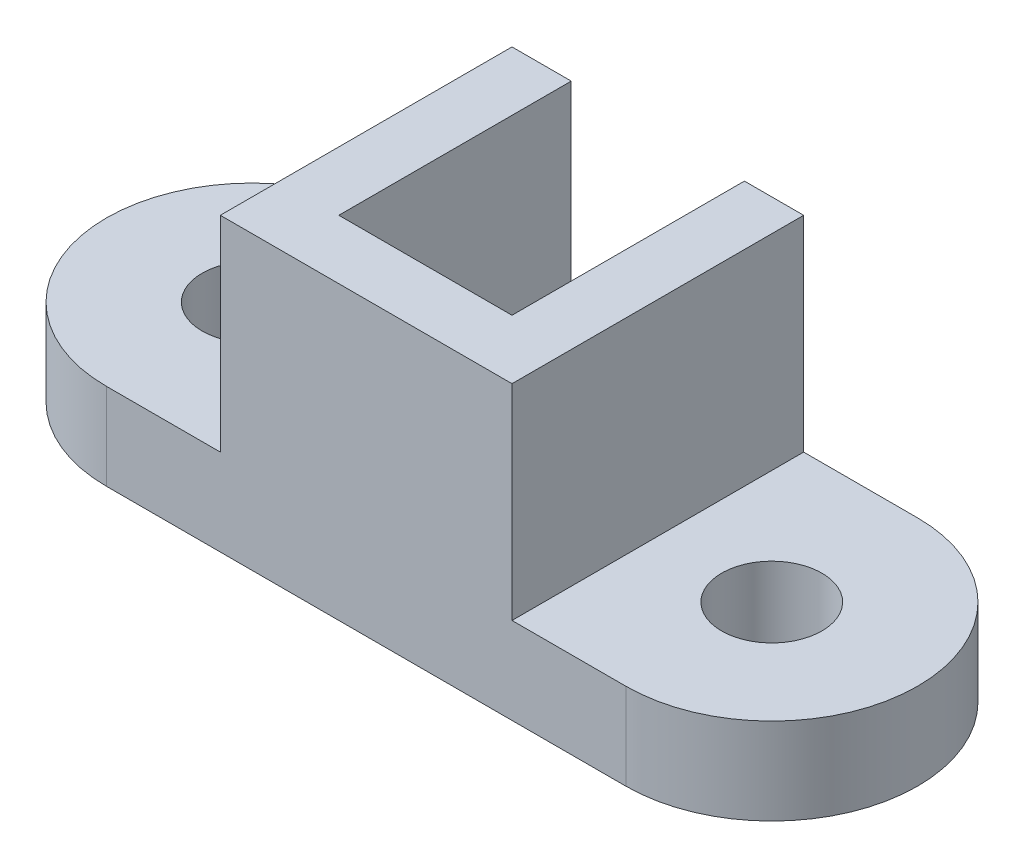
SolidWorks part; units mm, degrees
ref_plane "Front Plane" through (0, 0, 0) normal (0, 0, 1) x (1, 0, 0)
ref_plane "Top Plane" through (0, 0, 0) normal (0, 1, 0) x (1, 0, 0)
ref_plane "Right Plane" through (0, 0, 0) normal (1, 0, 0) x (0, 0, -1)
sketch "Sketch1" plane through (0, 0, 0) normal (0, 1, 0) x (1, 0, 0)
  line L0 (0, 0) -> (114, 0) construction
  line L1 (0, 32) -> (114, 32)
  line L2 (0, -32) -> (114, -32)
  arc A0 (0, 32) -> (0, -32) centre (0, 0) ccw
  arc A1 (114, -32) -> (114, 32) centre (114, 0) ccw
  point P3 (57, 0)
  dimension "D1" = 32
  dimension "D2" = 114
extrude "Boss-Extrude1" add sketch "Sketch1" along normal blind 19
sketch "Sketch2" plane through (0, 19, 0) normal (0, 1, 0) x (1, 0, 0)
  line L0 (0, 0) -> (114, 0) construction
  line L1 (57, 32) -> (57, -32) construction
  line L2 (114, 32) -> (0, 32) construction
  line L3 (0, -32) -> (114, -32) construction
  line L5 (25, 32) -> (89, 32)
  line L6 (25, 32) -> (25, -32)
  line L7 (25, -32) -> (89, -32)
  line L8 (89, 32) -> (89, -32)
  line L9 (25, 32) -> (89, -32) construction
  line L10 (25, -32) -> (89, 32) construction
  point P10 (57, 0)
  dimension "D1" = 64
extrude "Boss-Extrude2" add sketch "Sketch2" along normal blind 45
sketch "Sketch3" plane through (89, 0, 0) normal (1, 0, 0) x (0, 0, -1)
  line L0 (-19, 64) -> (32, 13)
  line L1 (-32, 64) -> (32, 64) construction
  line L2 (32, 19) -> (32, 0) construction
  line L3 (32, 13) -> (32, 64)
  line L4 (32, 64) -> (-19, 64)
  dimension "D1" = 13
  dimension "D2" = 13
extrude "Cut-Extrude1" cut sketch "Sketch3" against normal blind 38 from offset 13 offset against normal yes
sketch "Sketch4" plane through (0, 19, 0) normal (0, 1, 0) x (1, 0, 0)
  circle A0 centre (0, 0) radius 11
  dimension "D1" = 22
extrude "Cut-Extrude2" cut sketch "Sketch4" against normal through all
sketch "Sketch5" plane through (0, 19, 0) normal (0, 1, 0) x (1, 0, 0)
  circle A0 centre (114, 0) radius 11
  dimension "D1" = 22
extrude "Cut-Extrude3" cut sketch "Sketch5" against normal through all
